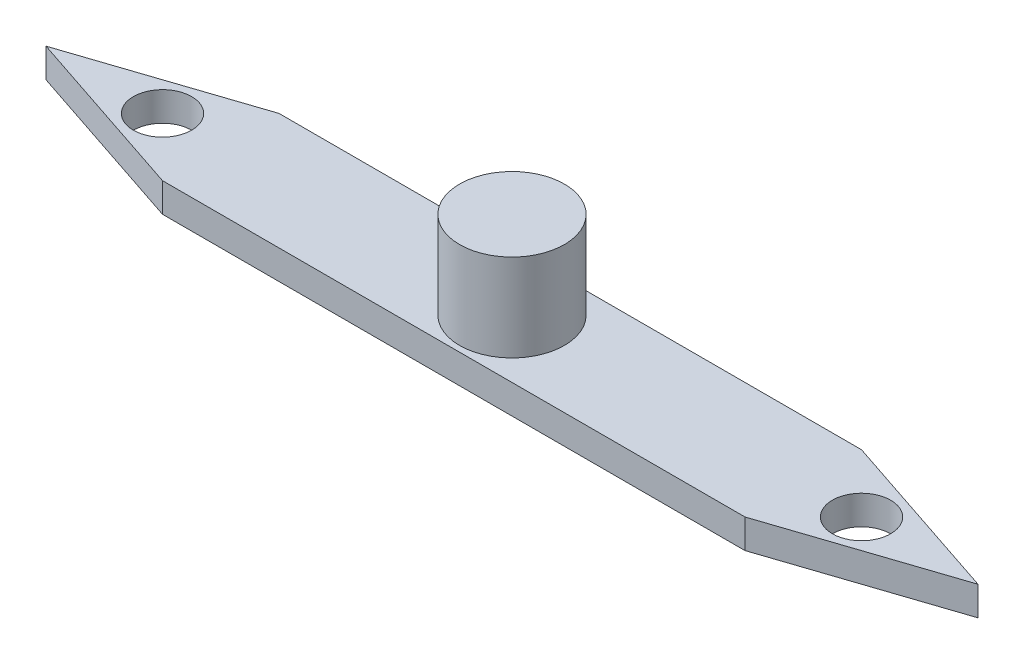
SolidWorks part; units mm, degrees
ref_plane "Front Plane" through (0, 0, 0) normal (0, 0, 1) x (1, 0, 0)
ref_plane "Top Plane" through (0, 0, 0) normal (0, 1, 0) x (1, 0, 0)
ref_plane "Right Plane" through (0, 0, 0) normal (1, 0, 0) x (0, 0, -1)
sketch "Sketch1" plane through (0, 0, 0) normal (0, 1, 0) x (1, 0, 0)
  line L0 (-50, 10) -> (0, 20)
  line L1 (-50, 10) -> (50, 10)
  line L2 (-50, 10) -> (-50, -10)
  line L3 (-50, -10) -> (50, -10)
  line L4 (50, 10) -> (50, -10)
  line L5 (-50, 10) -> (50, -10) construction
  line L6 (-50, -10) -> (50, 10) construction
  line L7 (0, 20) -> (50, 10)
  line L8 (50, -10) -> (0, -20)
  line L9 (0, -20) -> (-50, -10)
  line L10 (50, 10) -> (80, 0)
  line L11 (80, 0) -> (50, -10)
  line L12 (-50, 10) -> (-80, 0)
  line L13 (-80, 0) -> (-50, -10)
  point P0 (0, 0)
  dimension "D1" = 100
  dimension "D2" = 20
  dimension "D3" = 20
  dimension "D4" = 20
  dimension "D5" = 20
  dimension "D6" = 30
  dimension "D7" = 30
extrude "Boss-Extrude1" add sketch "Sketch1" along normal blind 5
sketch "Sketch3" plane through (0, 5, 0) normal (0, 1, 0) x (1, 0, 0)
  circle A0 centre (0, 0) radius 9
  dimension "D1" = 18
extrude "Boss-Extrude2" add sketch "Sketch3" along normal blind 15
sketch "Sketch5" plane through (0, 5, 0) normal (0, 1, 0) x (1, 0, 0)
  circle A0 centre (60, 0) radius 5
  circle A1 centre (-60, 0) radius 5
  dimension "D2" = 10
  dimension "D3" = 10
  dimension "D1" = 20
  dimension "D4" = 20
extrude "Cut-Extrude1" cut sketch "Sketch5" against normal blind 15
